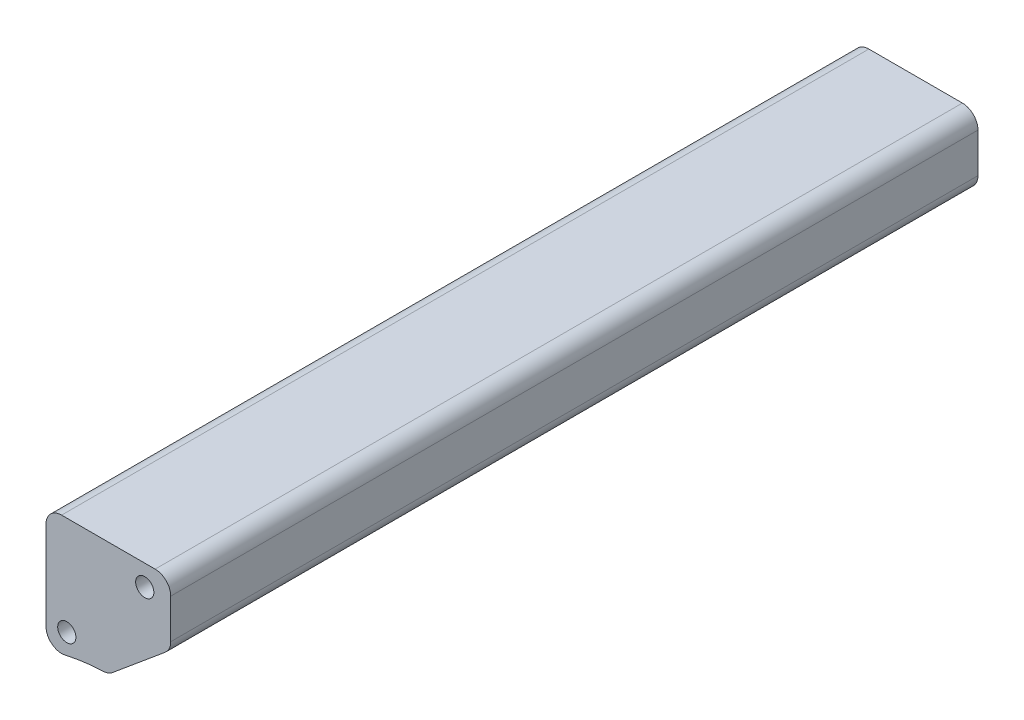
SolidWorks part; units mm, degrees
material "6061-T4 (SS)"
ref_plane "Front" through (0, 0, 0) normal (0, 0, 1) x (1, 0, 0)
ref_plane "Top" through (0, 0, 0) normal (0, 1, 0) x (1, 0, 0)
ref_plane "Right" through (0, 0, 0) normal (1, 0, 0) x (0, 0, -1)
sketch "Sketch1" plane through (0, 0, 0) normal (0, 0, 1) x (1, 0, 0)
  line L2 (0, 0) -> (0, 12)
  line L5 (0, 12) -> (12, 12)
  line L8 (12, 12) -> (12, 0) construction
  line L9 (6, 0.9985) -> (6, 12) construction
  line L10 (12, 6) -> (6, 0.9985)
  line L11 (12, 12) -> (12, 6)
  arc A3 (0, 0) -> (6, 0.9985) centre (6.245, -19) cw
  dimension "D1" = 6
  dimension "D3" = 6
  dimension "D5" = 20
  dimension "D6" = 31
  dimension "D2" = 12
  dimension "D4" = 12
extrude "Boss-Extrude1" add sketch "Sketch1" along normal blind 77.66
hole_wizard "M2.2x0.45 Tapped Hole1" positions "3DSketch1" profile "Sketch3" tap size "M2.2x0.45" standard "ANSI Metric"
sketch3d "3DSketch1"
  line L1 (12, 12, 77.66) -> (0, 12, 77.66) construction
  line L8 (12, 12, 0) -> (0, 12, 0) construction
  line L22 (6, 12, 77.66) -> (6, 0.9985, 77.66) construction
  line L24 (6, 12, 0) -> (6, 0.9985, 0) construction
  arc A7 (0, 0, 77.66) -> (6, 0.9985, 77.66) centre (6.245, -19, 77.66) ccw construction
  arc A8 (0, 0, 0) -> (6, 0.9985, 0) centre (6.245, -19, 0) ccw construction
  point P0 (2, 2.5, 77.66)
  point P2 (9.5, 10, 77.66)
  point P5 (2, 2.5, 0)
  point P7 (9.5, 10, 0)
  point P86 (6.245, -19, 57.66)
  point P93 (6.245, -19, -20)
  dimension "D1" = 3.5
  dimension "D2" = 2
  dimension "D3" = 4
  dimension "D6" = 4
  dimension "D4" = 9.5
  dimension "D5" = 3.5
  dimension "D7" = 9.5
  dimension "D8" = 2
cosmetic thread "Hole Thread1" parameters "D1"=9.55, "D2"=2
cosmetic thread "Hole Thread2" parameters "D1"=9.55, "D2"=2
cosmetic thread "Hole Thread3" parameters "D1"=9.55, "D2"=2
cosmetic thread "Hole Thread4" parameters "D1"=9.55, "D2"=2
sketch "Sketch3" plane through (2, 2.5, 77.66) normal (1, 0, 0) x (0, -1, 0)
  line L0 (0, 0) -> (0, 10.5258)
  line L1 (0, 10.5258) -> (0.875, 10)
  line L2 (0.875, 10) -> (0.875, 0)
  line L5 (0.875, 0) -> (0, 0)
  line L10 (0, 10.5258) -> (-0.875, 10) construction
  line L11 (0, -6.35) -> (0, 107.95) construction
  dimension "Tap Drill Dia." = 1.75
  dimension "Tap Drill Depth" = 10
  dimension "Drill Angle" = 118
fillet "Fillet1" radius 1.5 5 edges at (6, 0.9985, 38.83) (12, 6, 38.83) (12, 12, 38.83) (0, 0, 38.83) (0, 12, 38.83)
equation "\"D1@Boss-Extrude1\"=79-1.34"
